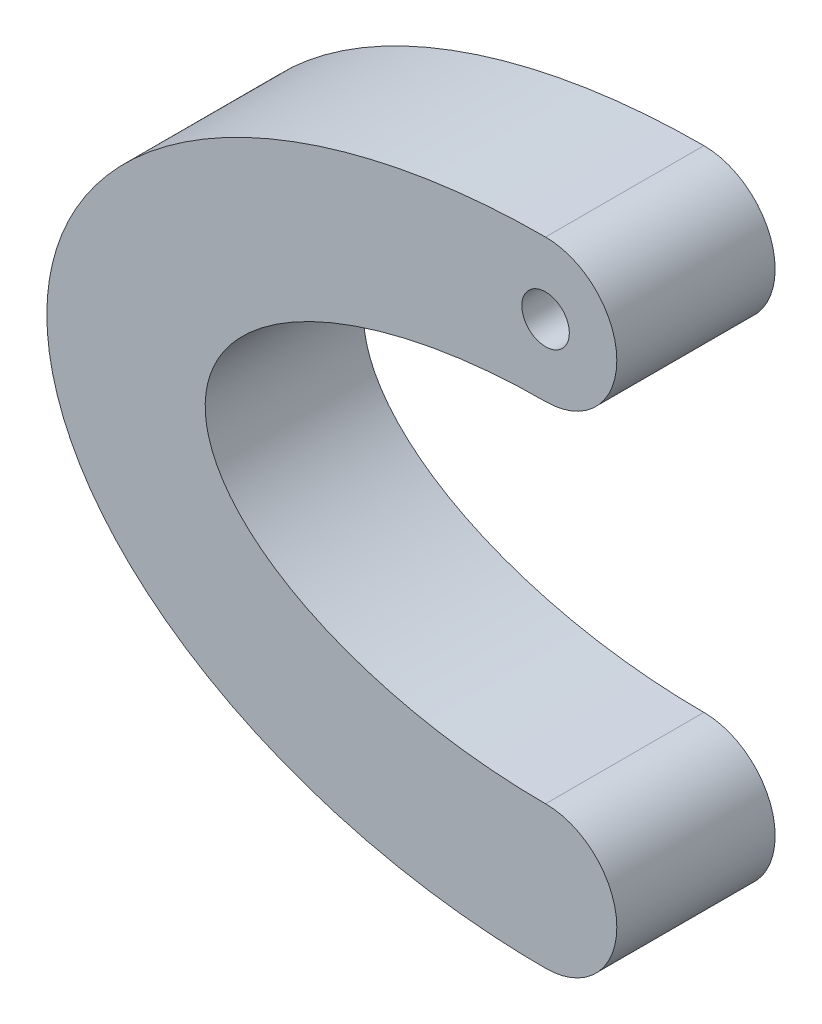
SolidWorks part; units mm, degrees
ref_plane "Front Plane" through (0, 0, 0) normal (0, 0, 1) x (1, 0, 0)
ref_plane "Top Plane" through (0, 0, 0) normal (0, 1, 0) x (1, 0, 0)
ref_plane "Right Plane" through (0, 0, 0) normal (1, 0, 0) x (0, 0, -1)
sketch "Sketch1" plane through (0, 0, 0) normal (0, 0, 1) x (1, 0, 0)
  line L0 (-0.515, 0) -> (0, 0)
  line L1 (0, 0) -> (-21.5, 0)
  arc A0 (0, 20) -> (0, 11) centre (0, 15.5) cw
  circle A2 centre (0, 15.5) radius 1.5
  arc A3 (0, -20) -> (0, -11) centre (0, -15.5) ccw
  ellipse E0 centre (0, 0) end of major axis (-31.5, 0) minor radius 20 (0, 20) -> (0, -20) ccw
  ellipse E1 centre (0, 0) end of major axis (-21.5, 0) minor radius 11 (0, -11) -> (0, 11) cw
  dimension "D3" = 4.5
  dimension "D5" = 10
  dimension "D4" = 3
  dimension "D1" = 31.5
  dimension "D2" = 20
extrude "Boss-Extrude1" add sketch "Sketch1" against normal blind 10 contours E1 A0 E0 A3 A2
